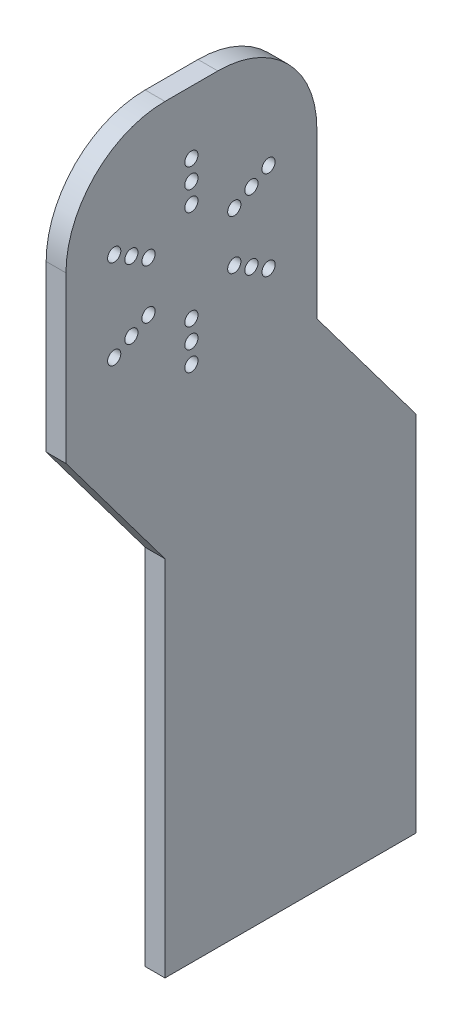
SolidWorks part; units mm, degrees
material "Polylactic Acid"
ref_plane "Front Plane" through (0, 0, 0) normal (0, 0, 1) x (1, 0, 0)
ref_plane "Top Plane" through (0, 0, 0) normal (0, 1, 0) x (1, 0, 0)
ref_plane "Right Plane" through (0, 0, 0) normal (1, 0, 0) x (0, 0, -1)
sketch "Sketch1" plane through (0, 0, 0) normal (0, 0, 1) x (1, 0, 0)
  line L0 (-4.85, -24) -> (4.85, -24) construction
  line L1 (-14, 27.5) -> (17, 27.5)
  line L2 (-14, 27.5) -> (-14, -27.5)
  line L3 (-14, -27.5) -> (17, -27.5)
  line L4 (17, 27.5) -> (17, -27.5)
  line L5 (-4.85, -24) -> (-4.85, 24) construction
  line L7 (-11, 22) -> (11, 22)
  line L8 (-11, 22) -> (-11, -22)
  line L9 (-11, -22) -> (11, -22)
  line L10 (11, 22) -> (11, -22)
  circle A0 centre (-4.85, -24) radius 1
  circle A1 centre (4.85, -24) radius 1
  circle A2 centre (4.85, 24) radius 1
  circle A3 centre (-4.85, 24) radius 1
  point P6 (0, -22)
  point P8 (-4.85, 0)
  point P12 (0, -24)
  point P22 (-11, 0)
  point P23 (11, 0)
  point P24 (17, 0)
  dimension "D5" = 2
  dimension "D3" = 9.7
  dimension "D4" = 48
  dimension "D6" = 44
  dimension "D7" = 22
  dimension "D8" = 55
  dimension "D9" = 3
  dimension "D10" = 6
  dimension "D1" = 2
  dimension "D2" = 2
extrude "Boss-Extrude1" add sketch "Sketch1" along normal blind 3
sketch "Sketch2" plane through (0, 0, 3) normal (0, 0, 1) x (1, 0, 0)
  line L0 (-14, -27.5) -> (17, -27.5) construction
  line L1 (14, 27.5) -> (17, 27.5)
  line L2 (14, 27.5) -> (14, -27.5)
  line L3 (14, -27.5) -> (17, -27.5)
  line L4 (17, 27.5) -> (17, -27.5)
  line L5 (17, -27.5) -> (17, 27.5) construction
  dimension "D1" = 3
extrude "Boss-Extrude2" add sketch "Sketch2" along normal blind 35
sketch "Sketch3" plane through (0, 27.5, 0) normal (0, 1, 0) x (1, 0, 0)
  line L0 (17, -38) -> (14, -38) construction
  line L1 (14, 0) -> (17, 0)
  line L2 (14, 0) -> (14, -53)
  line L3 (14, -53) -> (17, -53)
  line L4 (17, 0) -> (17, -53)
  line L5 (14, -38) -> (14, -3) construction
  dimension "D1" = 15
extrude "Boss-Extrude3" add sketch "Sketch3" along normal blind 20
sketch "Sketch4" plane through (14, 0, 0) normal (-1, 0, 0) x (0, 0, 1)
  line L0 (53, 27.5) -> (38, 27.5)
  line L1 (38, 27.5) -> (53, 47.5)
  line L2 (53, 47.5) -> (53, 27.5)
  line L3 (0, 27.5) -> (0, 47.5)
  line L4 (0, 47.5) -> (15, 47.5)
  line L5 (0, 47.5) -> (53, 47.5) construction
  line L6 (15, 47.5) -> (0, 27.5)
extrude "Cut-Extrude1" cut sketch "Sketch4" against normal up to surface (3 mm away) up to face at (17, 15.8333, 30.3333)
sketch "Sketch5" plane through (0, 47.5, 0) normal (0, 1, 0) x (1, 0, 0)
  line L1 (14, -15) -> (17, -15)
  line L2 (14, -15) -> (14, -53)
  line L3 (14, -53) -> (17, -53)
  line L4 (17, -15) -> (17, -53)
extrude "Boss-Extrude4" add sketch "Sketch5" along normal blind 40
sketch "Sketch6" plane through (-14, 0, 0) normal (-1, 0, 0) x (0, 0, 1)
  line L0 (34, 72) -> (34, 75) construction
  line L1 (34, 64.5) -> (34, 72) construction
  line L2 (15, 87.5) -> (53, 87.5) construction
  circle A0 centre (34, 72) radius 1
  circle A1 centre (34, 75) radius 1
  circle A2 centre (34, 78) radius 1
  circle A3 centre (45.6913, 71.25) radius 1
  circle A4 centre (43.0933, 69.75) radius 1
  circle A5 centre (40.4952, 68.25) radius 1
  circle A6 centre (45.6913, 57.75) radius 1
  circle A7 centre (43.0933, 59.25) radius 1
  circle A8 centre (40.4952, 60.75) radius 1
  circle A9 centre (34, 51) radius 1
  circle A10 centre (34, 54) radius 1
  circle A11 centre (34, 57) radius 1
  circle A12 centre (22.3087, 57.75) radius 1
  circle A13 centre (24.9067, 59.25) radius 1
  circle A14 centre (27.5048, 60.75) radius 1
  circle A15 centre (22.3087, 71.25) radius 1
  circle A16 centre (24.9067, 69.75) radius 1
  circle A17 centre (27.5048, 68.25) radius 1
  point P45 (34, 87.5)
  dimension "D3" = 2
  dimension "D2" = 3
  dimension "D5" = 7.5
  dimension "D6" = 23
  dimension "D1" = 3
  dimension "D4" = 6
extrude "Cut-Extrude2" cut sketch "Sketch6" against normal up to surface (31 mm away) up to face at (17, 33.75, 26.5)
fillet "Fillet1" radius 15 2 edges at (15.5, 87.5, 53) (15.5, 87.5, 15)
